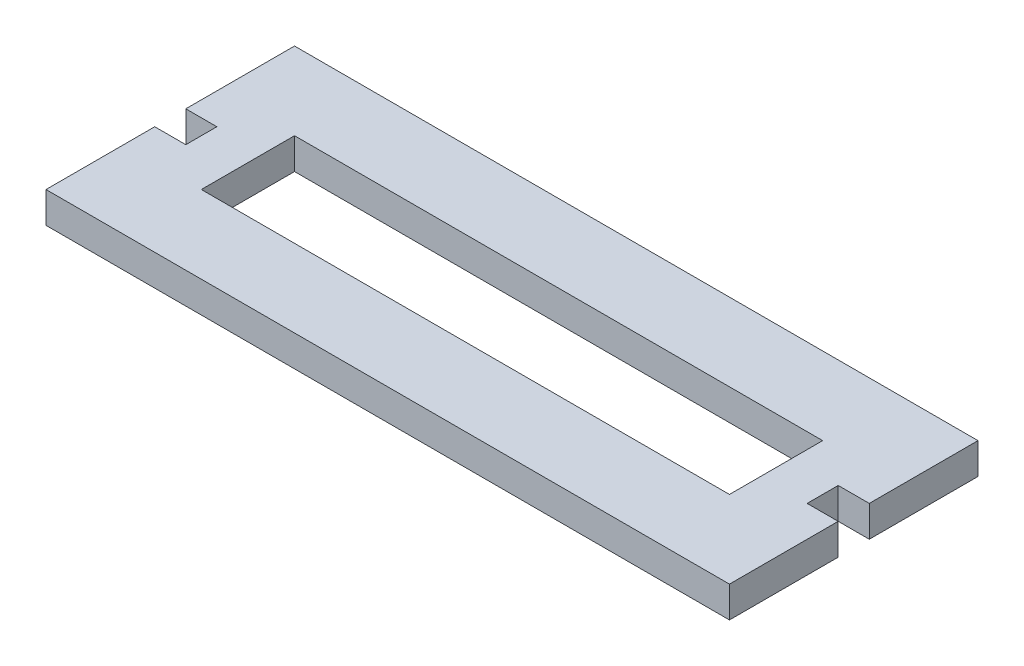
SolidWorks part; units mm, degrees
ref_plane "Front Plane" through (0, 0, 0) normal (0, 0, 1) x (1, 0, 0)
ref_plane "Top Plane" through (0, 0, 0) normal (0, 1, 0) x (1, 0, 0)
ref_plane "Right Plane" through (0, 0, 0) normal (1, 0, 0) x (0, 0, -1)
sketch "Sketch1" plane through (0, 0, 0) normal (0, 1, 0) x (1, 0, 0)
  line L0 (-3.175, 0) -> (-3.175, 25.4)
  line L1 (0, 0) -> (63.5, 0)
  line L2 (0, 0) -> (0, 25.4)
  line L3 (0, 25.4) -> (63.5, 25.4)
  line L4 (63.5, 0) -> (63.5, 25.4)
  line L5 (63.5, 0) -> (66.675, 0)
  line L6 (66.675, 0) -> (66.675, 25.4)
  line L8 (63.5, 25.4) -> (66.675, 25.4)
  line L9 (66.675, 25.4) -> (66.675, 0)
  line L10 (0, 25.4) -> (-3.175, 25.4)
  line L11 (66.675, -3.175) -> (66.675, 28.575) construction
  line L12 (-3.175, -3.175) -> (-3.175, 28.575) construction
  line L13 (-3.175, 28.575) -> (66.675, 28.575) construction
  line L14 (0, 0) -> (-3.175, 0)
  line L15 (-55, 0) -> (55, 0) construction
  line L16 (-3.175, 14.2875) -> (0, 14.2875)
  line L17 (-3.175, -3.175) -> (66.675, -3.175) construction
  line L18 (-3.175, 14.2875) -> (-3.175, 11.1125)
  line L19 (-3.175, 11.1125) -> (0, 11.1125)
  line L20 (0, 14.2875) -> (0, 11.1125)
  line L21 (63.5, 14.2875) -> (66.675, 14.2875)
  line L22 (63.5, 14.2875) -> (63.5, 11.1125)
  line L23 (63.5, 11.1125) -> (66.675, 11.1125)
  line L24 (66.675, 14.2875) -> (66.675, 11.1125)
  dimension "D2" = 63.5
  dimension "D3" = 3.175
  dimension "D4" = 3.175
  dimension "D5" = 11.1125
  dimension "D6" = 11.1125
  dimension "D1" = 3.175
extrude "Boss-Extrude1" add sketch "Sketch1" along normal blind 3.175 contours L1 L4 L3 L2 | L0 L16 L2 L10 | L19 L0 L14 L2 | L4 L21 L9 L8 | L23 L4 L5 L6
sketch "Sketch2" plane through (0, 3.175, 0) normal (0, 1, 0) x (1, 0, 0)
  line L0 (-3.175, 0) -> (66.675, 0) construction
  line L1 (4.7625, 7.9375) -> (58.7375, 7.9375)
  line L2 (4.7625, 7.9375) -> (4.7625, 17.4625)
  line L3 (4.7625, 17.4625) -> (58.7375, 17.4625)
  line L4 (58.7375, 7.9375) -> (58.7375, 17.4625)
  line L5 (-3.175, 14.2875) -> (-3.175, 25.4) construction
  dimension "D1" = 9.525
  dimension "D2" = 7.9375
  dimension "D3" = 53.975
  dimension "D4" = 7.9375
extrude "Cut-Extrude1" cut sketch "Sketch2" against normal through all
